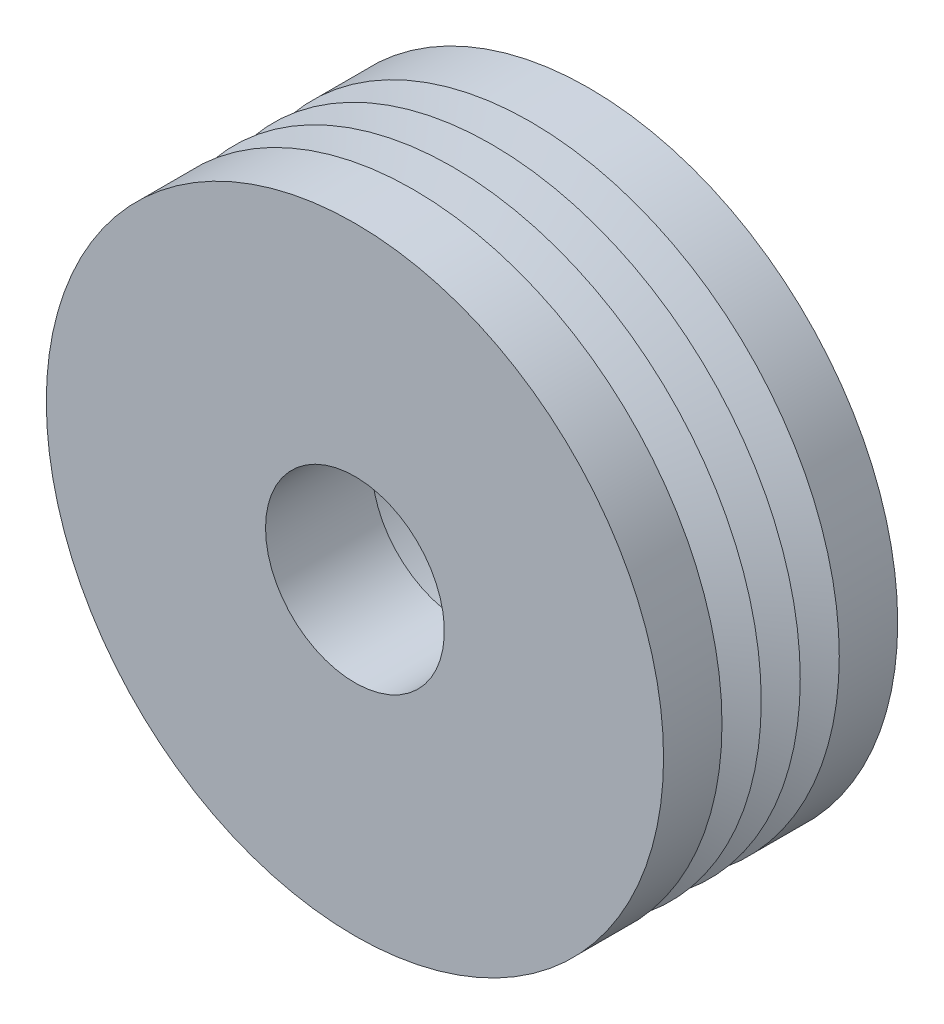
SolidWorks part; units mm, degrees
material "Caucho"
ref_plane "Alzado" through (0, 0, 0) normal (0, 0, 1) x (1, 0, 0)
ref_plane "Planta" through (0, 0, 0) normal (0, 1, 0) x (1, 0, 0)
ref_plane "Vista lateral" through (0, 0, 0) normal (1, 0, 0) x (0, 0, -1)
sketch "Sketch2" plane through (0, 0, 0) normal (0, 1, 0) x (1, 0, 0)
  line L0 (0, -272.1142) -> (0, 13333.5973) construction
  line L1 (0, 5.5) -> (-7.25, 5.5)
  line L2 (-7.25, 5.5) -> (-7.25, 4.1276)
  line L3 (-7.25, 0) -> (0, 0)
  line L4 (-6.25, 5.5) -> (-6.25, 0) construction
  line L5 (-7.25, 4.1276) -> (-6.25, 3.6667)
  line L6 (-6.25, 3.6667) -> (-7.25, 3.211)
  line L7 (-7.25, 3.211) -> (-6.25, 2.7552)
  line L8 (-6.25, 2.7552) -> (-7.25, 2.2943)
  line L9 (-7.25, 2.2943) -> (-6.25, 1.8333)
  line L10 (-6.25, 1.8333) -> (-7.25, 1.3724)
  line L11 (-6.25, 3.6667) -> (0, 3.6667) construction
  line L12 (-7.25, 1.3724) -> (-7.25, 0)
  line L13 (0, 5.5) -> (0, 0)
  point P11 (0, 0)
  point P18 (0, 0)
  point P19 (-7.25, 2.3125)
  point P20 (-6.4386, 2.7552)
  point P21 (-7.25, 1.1258)
  point P22 (-7.25, 2.3015)
  dimension "D1" = 14.5
  dimension "D2" = 5.5
  dimension "D3" = 1.8333
  dimension "D4" = 1.8333
  dimension "D5" = 1
revolve "Revolve1" add sketch "Sketch2" angle 360 about L13
sketch "Sketch3" plane through (0, 0, -5.5) normal (0, 0, -1) x (-1, 0, 0)
  circle A0 centre (0, 0) radius 4.5
  dimension "D1" = 9
extrude "Cut-Extrude1" cut sketch "Sketch3" against normal blind 3
sketch "Sketch4" plane through (0, 0, -2.5) normal (0, 0, -1) x (-1, 0, 0)
  circle A0 centre (0, 0) radius 2.1
extrude "Cut-Extrude2" cut sketch "Sketch4" against normal through all
